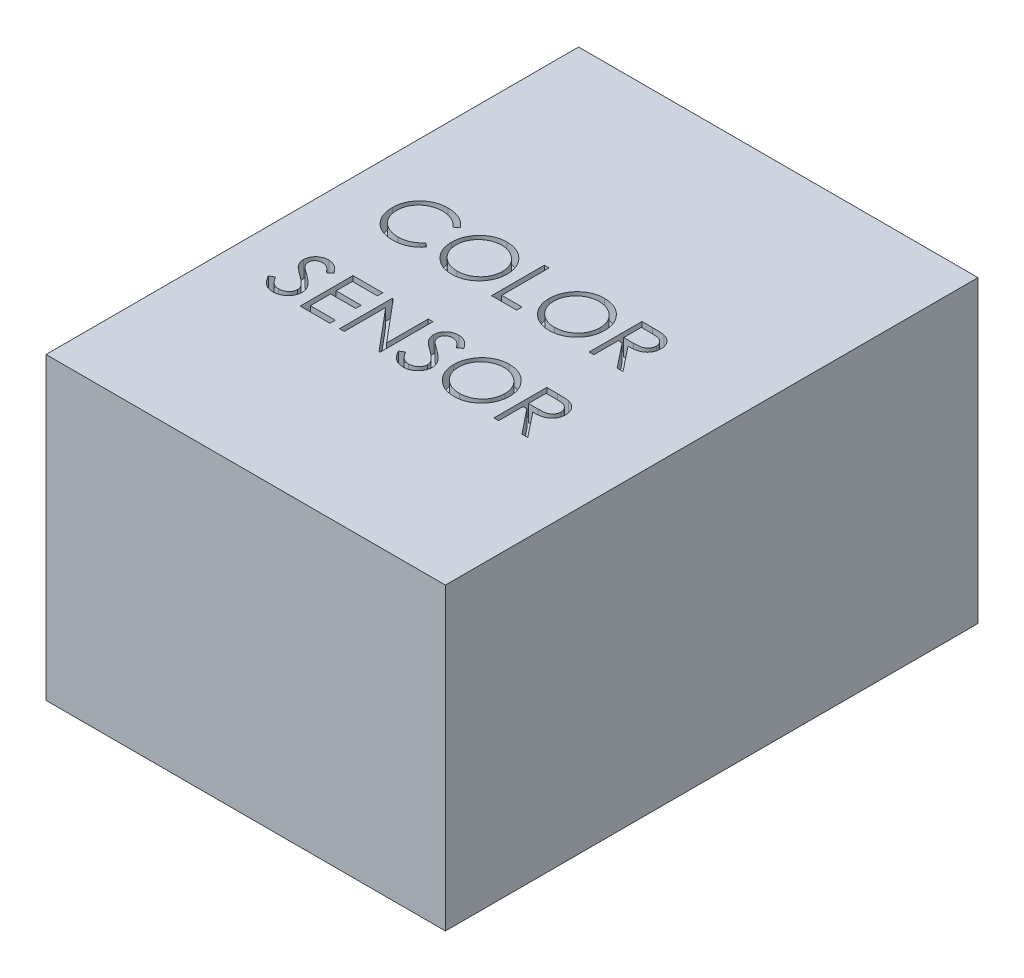
SolidWorks part; units mm, degrees
ref_plane "Front Plane" through (0, 0, 0) normal (0, 0, 1) x (1, 0, 0)
ref_plane "Top Plane" through (0, 0, 0) normal (0, 1, 0) x (1, 0, 0)
ref_plane "Right Plane" through (0, 0, 0) normal (1, 0, 0) x (0, 0, -1)
sketch "Sketch2" plane through (0, 0, 0) normal (0, 1, 0) x (1, 0, 0)
  line L1 (-12, -16) -> (12, -16)
  line L2 (-12, -16) -> (-12, 16)
  line L3 (-12, 16) -> (12, 16)
  line L4 (12, -16) -> (12, 16)
  line L5 (-12, -16) -> (12, 16) construction
  line L6 (-12, 16) -> (12, -16) construction
  point P0 (0, 0)
  dimension "D1" = 24
  dimension "D2" = 32
extrude "Boss-Extrude1" add sketch "Sketch2" along normal blind 18
sketch "Sketch3" plane through (0, 18, 0) normal (0, 1, 0) x (1, 0, 0)
  text T0 "COLOR \r\nSENSOR "
extrude "Cut-Extrude1" cut sketch "Sketch3" against normal blind 1
